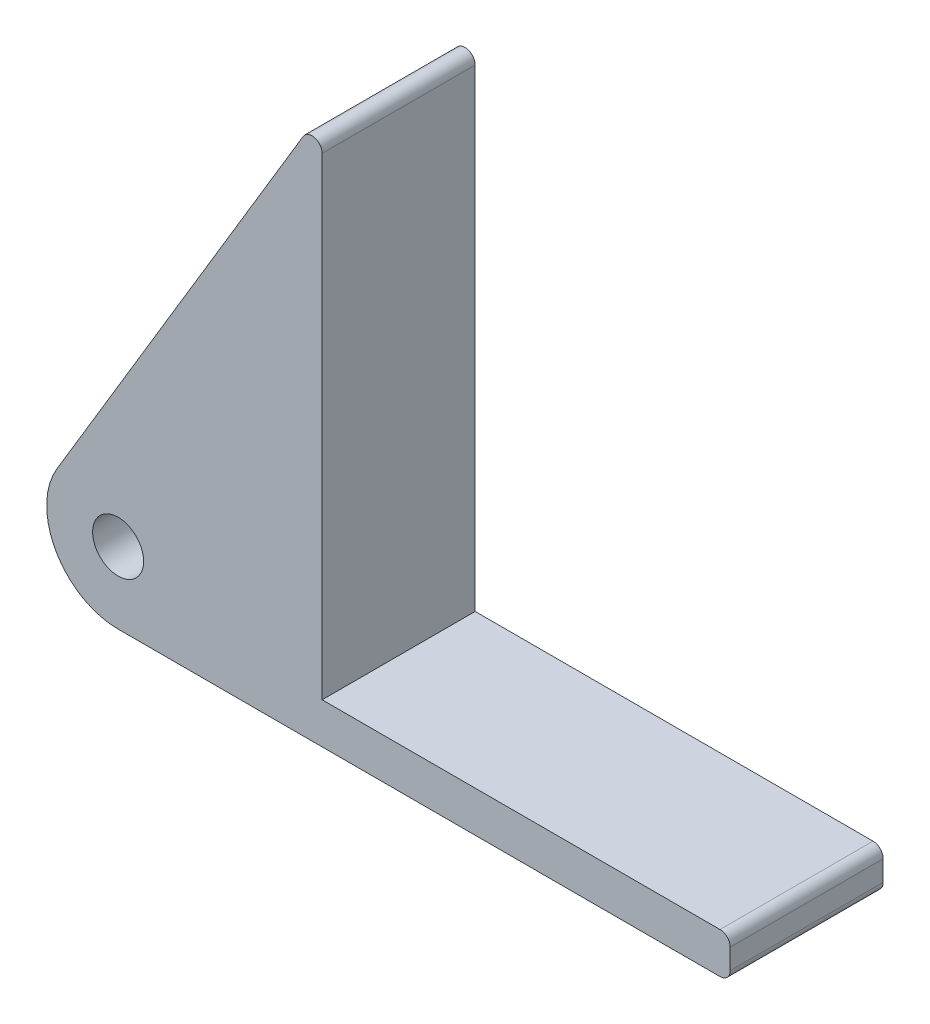
SolidWorks part; units mm, degrees
ref_plane "Plan de face" through (0, 0, 0) normal (0, 0, 1) x (1, 0, 0)
ref_plane "Plan de dessus" through (0, 0, 0) normal (0, 1, 0) x (1, 0, 0)
ref_plane "Plan de droite" through (0, 0, 0) normal (1, 0, 0) x (0, 0, -1)
sketch "Esquisse1" plane through (0, 0, 0) normal (0, 0, 1) x (1, 0, 0)
  line L0 (0, -7) -> (60, -7)
  line L1 (60, -7) -> (60, -3)
  line L2 (60, -3) -> (20, -3)
  line L3 (0, 0) -> (69.3491, 0) construction
  line L4 (20, -3) -> (20, 0)
  line L5 (20, 0) -> (20, 47)
  line L6 (20, 47) -> (-6.0047, 3.5977)
  circle A0 centre (0, 0) radius 2.5
  circle A1 centre (0, 0) radius 7
  dimension "D1" = 5
  dimension "D2" = 14
  dimension "D3" = 4
  dimension "D4" = 40
  dimension "D5" = 60
  dimension "D6" = 47
extrude "Boss.-Extru.1" add sketch "Esquisse1" against normal blind 15
fillet "Congé1" radius 1 3 edges at (60, -7, -7.5) (60, -3, -7.5) (20, 47, -7.5)
